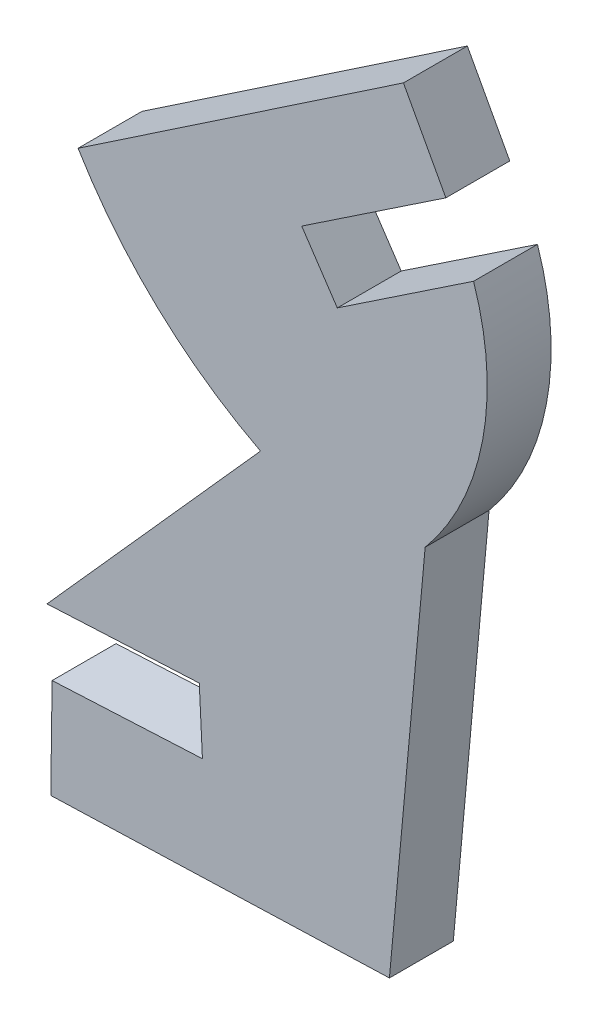
SolidWorks part; units mm, degrees
ref_plane "Front" through (0, 0, 0) normal (0, 0, 1) x (1, 0, 0)
ref_plane "Top" through (0, 0, 0) normal (0, 1, 0) x (1, 0, 0)
ref_plane "Right" through (0, 0, 0) normal (1, 0, 0) x (0, 0, -1)
sketch "Sketch1" plane through (0, 0, 0) normal (0, 0, 1) x (1, 0, 0)
  line L0 (171.193, -40.6651) -> (172.87, -22.3151)
  line L1 (165.1406, -22.2711) -> (155.1188, -33.4939)
  line L2 (155.2956, -41.1939) -> (171.193, -40.6651)
  line L3 (155.1188, -33.4939) -> (162.2669, -33.1404)
  line L4 (162.2669, -33.1404) -> (162.4152, -36.1404)
  line L5 (162.4152, -36.1404) -> (155.3594, -36.4894)
  line L6 (155.3594, -36.4894) -> (155.2956, -41.1939)
  line L7 (173.8419, -7.6271) -> (171.8504, -3.9497)
  line L8 (171.8504, -3.9497) -> (156.5781, -14.242)
  line L9 (175.1429, -10.3663) -> (168.7448, -14.6496)
  line L10 (168.7448, -14.6496) -> (167.0759, -12.1567)
  line L11 (167.0759, -12.1567) -> (173.8419, -7.6271)
  arc A0 (156.5781, -14.242) -> (165.1406, -22.2711) centre (175.0209, -3.154) ccw
  arc A1 (172.87, -22.3151) -> (175.1429, -10.3663) centre (163.3243, -14.3087) ccw
  dimension "D1" = 3
  dimension "D2" = 3
extrude "Base-Extrude" add sketch "Sketch1" along normal blind 3
